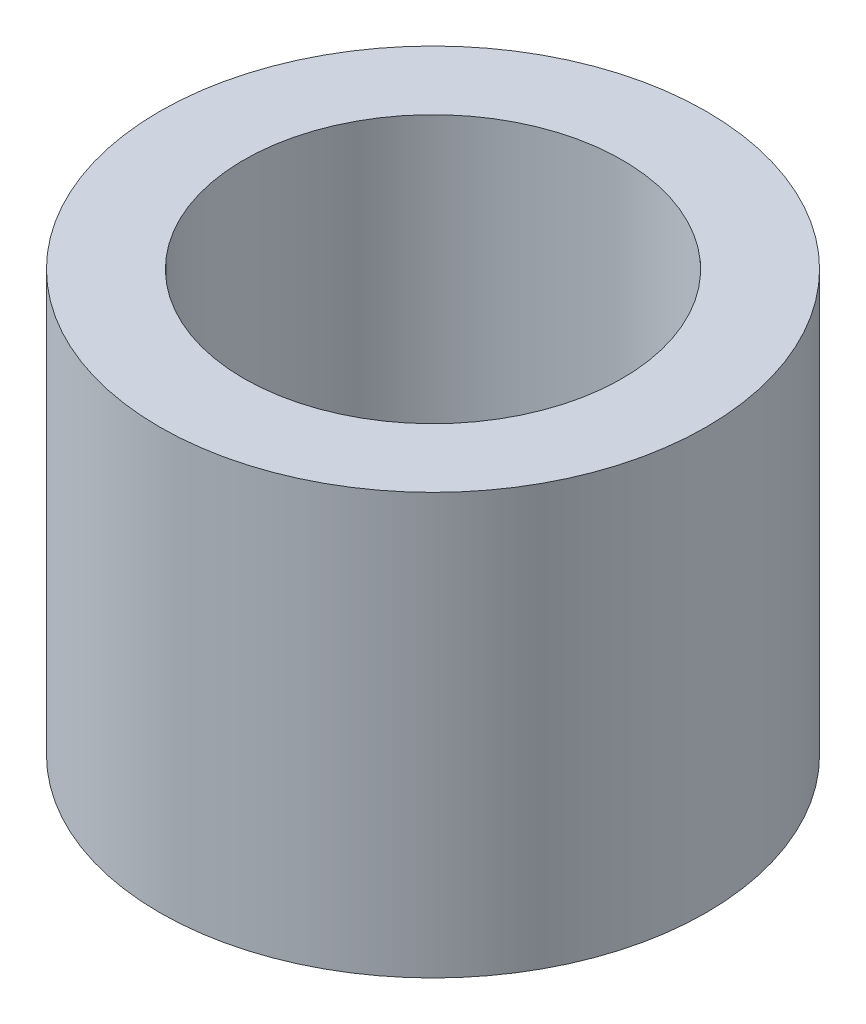
SolidWorks part; units mm, degrees
ref_plane "前视基准面" through (0, 0, 0) normal (0, 0, 1) x (1, 0, 0)
ref_plane "上视基准面" through (0, 0, 0) normal (0, 1, 0) x (1, 0, 0)
ref_plane "右视基准面" through (0, 0, 0) normal (1, 0, 0) x (0, 0, -1)
sketch "草图1" plane through (0, 0, 0) normal (0, 1, 0) x (1, 0, 0)
  circle A0 centre (0, 0) radius 2.25
  circle A1 centre (0, 0) radius 3.25
  dimension "D1" = 4.5
  dimension "D2" = 6.5
extrude "凸台-拉伸1" add sketch "草图1" along normal blind 5
